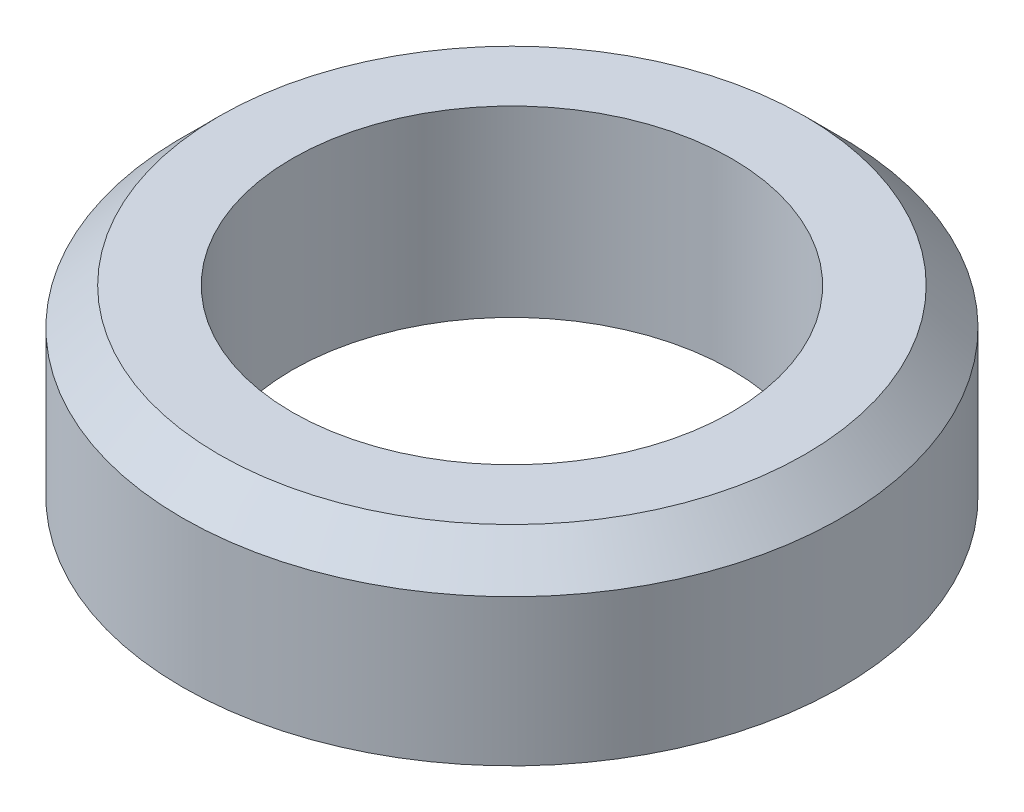
SolidWorks part; units mm, degrees
ref_plane "Спереди" through (0, 0, 0) normal (0, 0, 1) x (1, 0, 0)
ref_plane "Сверху" through (0, 0, 0) normal (0, 1, 0) x (1, 0, 0)
ref_plane "Справа" through (0, 0, 0) normal (1, 0, 0) x (0, 0, -1)
sketch "Эскиз1" plane through (0, 0, 0) normal (0, 1, 0) x (1, 0, 0)
  circle A0 centre (0, 0) radius 3
  circle A1 centre (0, 0) radius 4.5
  dimension "D1" = 6
  dimension "D2" = 9
extrude "Бобышка-Вытянуть1" add sketch "Эскиз1" along normal blind 2.5
chamfer "Фаска1" distance 0.5 angle 45 1 edges at (0, 2.5, 4.5)
